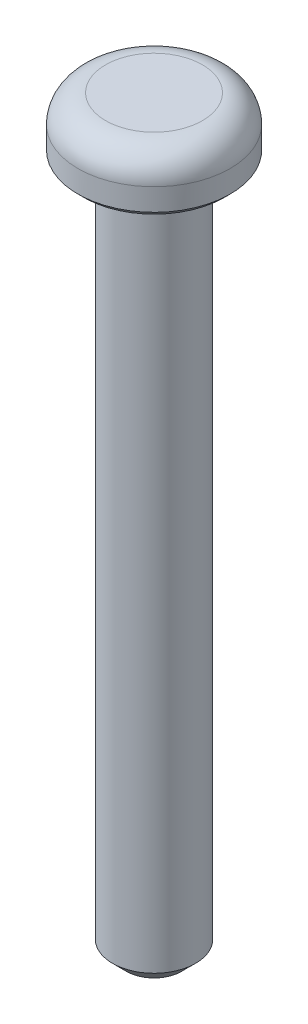
SolidWorks part; units mm, degrees
ref_plane "Front Plane" through (0, 0, 0) normal (0, 0, 1) x (1, 0, 0)
ref_plane "Top Plane" through (0, 0, 0) normal (0, 1, 0) x (1, 0, 0)
ref_plane "Right Plane" through (0, 0, 0) normal (1, 0, 0) x (0, 0, -1)
sketch "Sketch1" plane through (0, 0, 0) normal (0, 0, 1) x (1, 0, 0)
  line L0 (0, 0) -> (0, 27)
  line L1 (0, 27) -> (2.75, 27)
  line L2 (2.75, 27) -> (2.75, 25)
  line L3 (2.75, 25) -> (1.5, 25)
  line L4 (1.5, 25) -> (1.5, 0)
  line L5 (1.5, 0) -> (0, 0)
  dimension "D1" = 1.5
  dimension "D2" = 2.75
  dimension "D3" = 2
  dimension "D4" = 25
revolve "Revolve1" add sketch "Sketch1" angle 360 about L0
fillet "Fillet1" radius 1 1 edges at (0, 27, -2.75)
chamfer "Chamfer1" distance 0.5 angle 45 1 edges at (0, 0, -1.5)
chamfer "Chamfer2" distance 0.2 angle 45 1 edges at (0, 25, -2.75)
